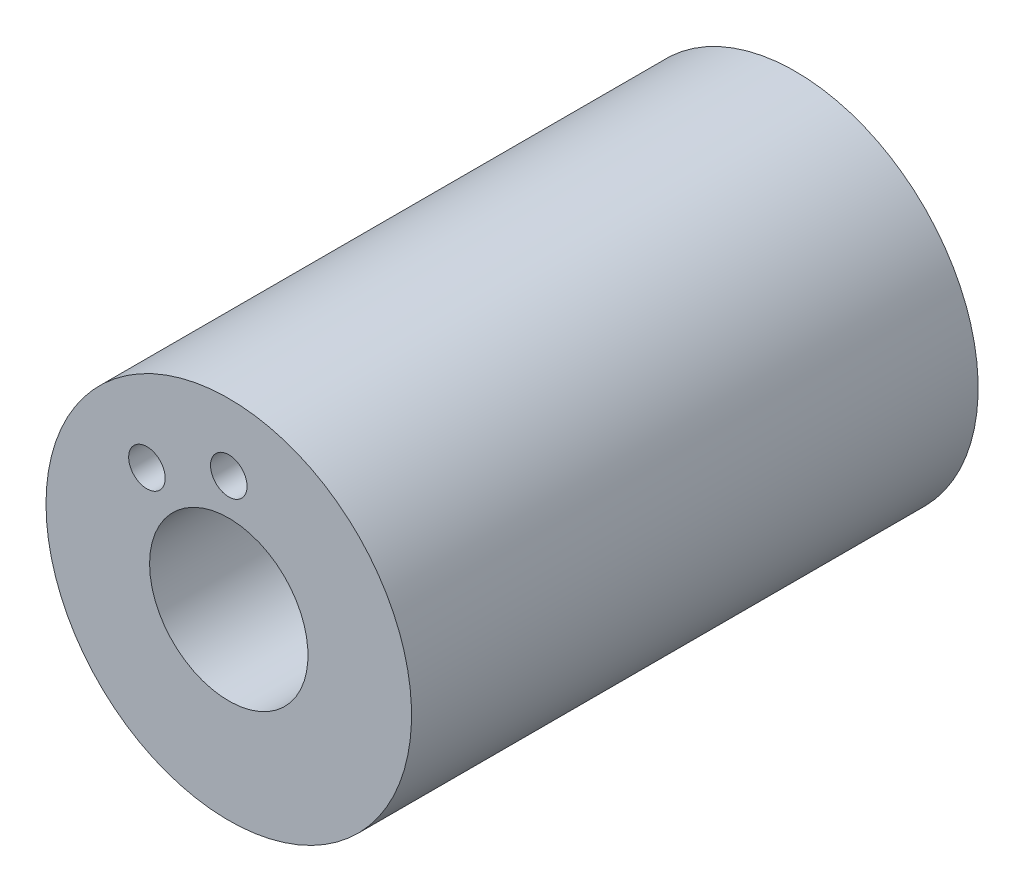
SolidWorks part; units mm, degrees
material "Plain Carbon Steel"
ref_plane "Front Plane" through (0, 0, 0) normal (0, 0, 1) x (1, 0, 0)
ref_plane "Top Plane" through (0, 0, 0) normal (0, 1, 0) x (1, 0, 0)
ref_plane "Right Plane" through (0, 0, 0) normal (1, 0, 0) x (0, 0, -1)
sketch "Sketch1" plane through (0, 0, 0) normal (0, 0, 1) x (1, 0, 0)
  line L0 (0, 0) -> (0, 50000) construction
  line L1 (-0.5228, 0.5228) -> (-35177.2244, 35177.2244) construction
  circle A0 centre (0, 0) radius 15
  circle A1 centre (0, 0) radius 6.5
  circle A2 centre (0, 0) radius 9.5 construction
  circle A3 centre (0, 9.5) radius 1.5
  circle A4 centre (-6.7175, 6.7175) radius 1.5
  point P14 (-2.9677, 9.0246)
  dimension "D1" = 30
  dimension "D2" = 19
  dimension "D3" = 13
  dimension "D4" = 3
  dimension "D5" = 45
extrude "Boss-Extrude1" add sketch "Sketch1" along normal mid plane 46.5
